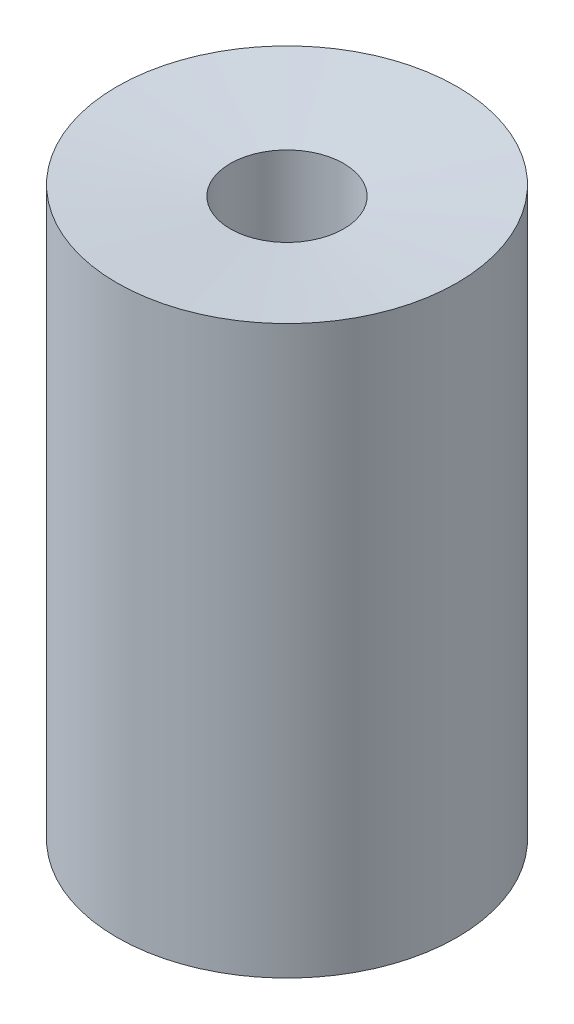
SolidWorks part; units mm, degrees
material "RNX-ELF"
ref_plane "Front Plane" through (0, 0, 0) normal (0, 0, 1) x (1, 0, 0)
ref_plane "Top Plane" through (0, 0, 0) normal (0, 1, 0) x (1, 0, 0)
ref_plane "Right Plane" through (0, 0, 0) normal (1, 0, 0) x (0, 0, -1)
sketch "Sketch1" plane through (0, 0, 0) normal (0, 1, 0) x (1, 0, 0)
  circle A0 centre (0, 0) radius 30
  circle A1 centre (0, 0) radius 10
  dimension "D1" = 60
  dimension "D2" = 20
extrude "Extrude1" add sketch "Sketch1" along normal blind 100
sketch "Sketch2" [suppressed] plane through (0, 38, 0) normal (0, 1, 0) x (-1, 0, 0)
  circle A0 centre (-3.0948, -18.3848) radius 3.8024
sketch "Sketch3" plane through (0, 0, 0) normal (0, 0, 1) x (1, 0, 0)
  line L0 (-30, 100) -> (0, 97.3753)
  line L1 (30, 100) -> (-30, 100) construction
  line L2 (0, 97.3753) -> (0, 100)
  line L3 (10, 100) -> (-10, 100) construction
  line L4 (0, 100) -> (-30, 100)
  line L5 (-30, 50) -> (30, 50) construction
  line L6 (-30, 100) -> (-30, 0) construction
  line L7 (30, 0) -> (30, 100) construction
  line L8 (0, 2.6247) -> (0, 0)
  line L9 (0, 0) -> (-30, 0)
  line L10 (-30, 0) -> (0, 2.6247)
  dimension "D1" = 5
revolve "Cut-Revolve1" cut sketch "Sketch3" angle 360 about L2
